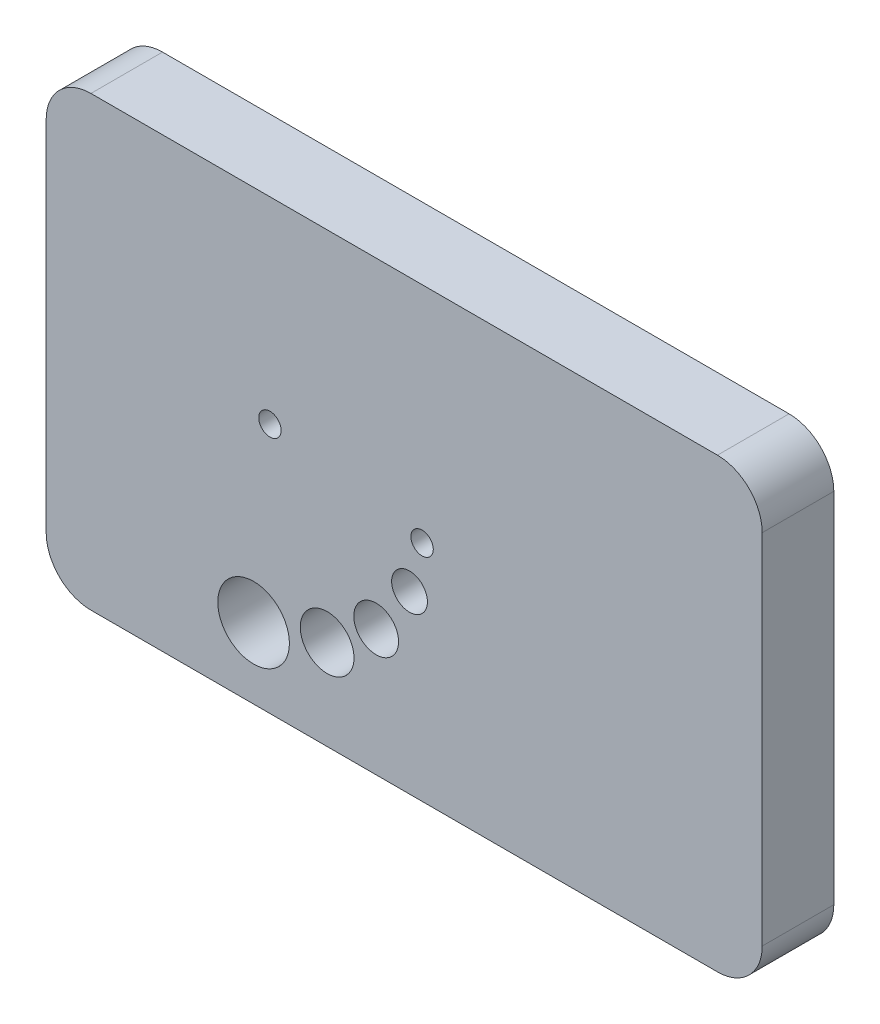
SolidWorks part; units mm, degrees
ref_plane "Front Plane" through (0, 0, 0) normal (0, 0, 1) x (1, 0, 0)
ref_plane "Top Plane" through (0, 0, 0) normal (0, 1, 0) x (1, 0, 0)
ref_plane "Right Plane" through (0, 0, 0) normal (1, 0, 0) x (0, 0, -1)
sketch "Sketch1" plane through (0, 0, 0) normal (0, 0, 1) x (1, 0, 0)
  line L1 (0, 0) -> (80, 0)
  line L2 (0, 0) -> (0, 50)
  line L3 (0, 50) -> (80, 50)
  line L4 (80, 0) -> (80, 50)
  circle A0 centre (25, 28) radius 1.25
  circle A1 centre (25, 28) radius 15 construction
  circle A2 centre (42, 25) radius 1.25
  circle A3 centre (40.5955, 19.5984) radius 2
  circle A4 centre (36.8701, 14.1199) radius 2.5
  circle A5 centre (31.3916, 10.0657) radius 3
  circle A6 centre (23.1738, 7.8743) radius 4
  point P10 (23.1738, 7.8743)
  dimension "D3" = 2.5
  dimension "D4" = 30
  dimension "D5" = 2.5
  dimension "D7" = 17
  dimension "D8" = 25
  dimension "D9" = 25
  dimension "D11" = 4
  dimension "D12" = 5
  dimension "D13" = 6
  dimension "D10" = 8
  dimension "D1" = 80
  dimension "D2" = 50
  dimension "D6" = 3
extrude "Boss-Extrude1" add sketch "Sketch1" along normal blind 8
fillet "Fillet1" radius 5 4 edges at (0, 50, 4) (80, 50, 4) (80, 0, 4) (0, 0, 4)
